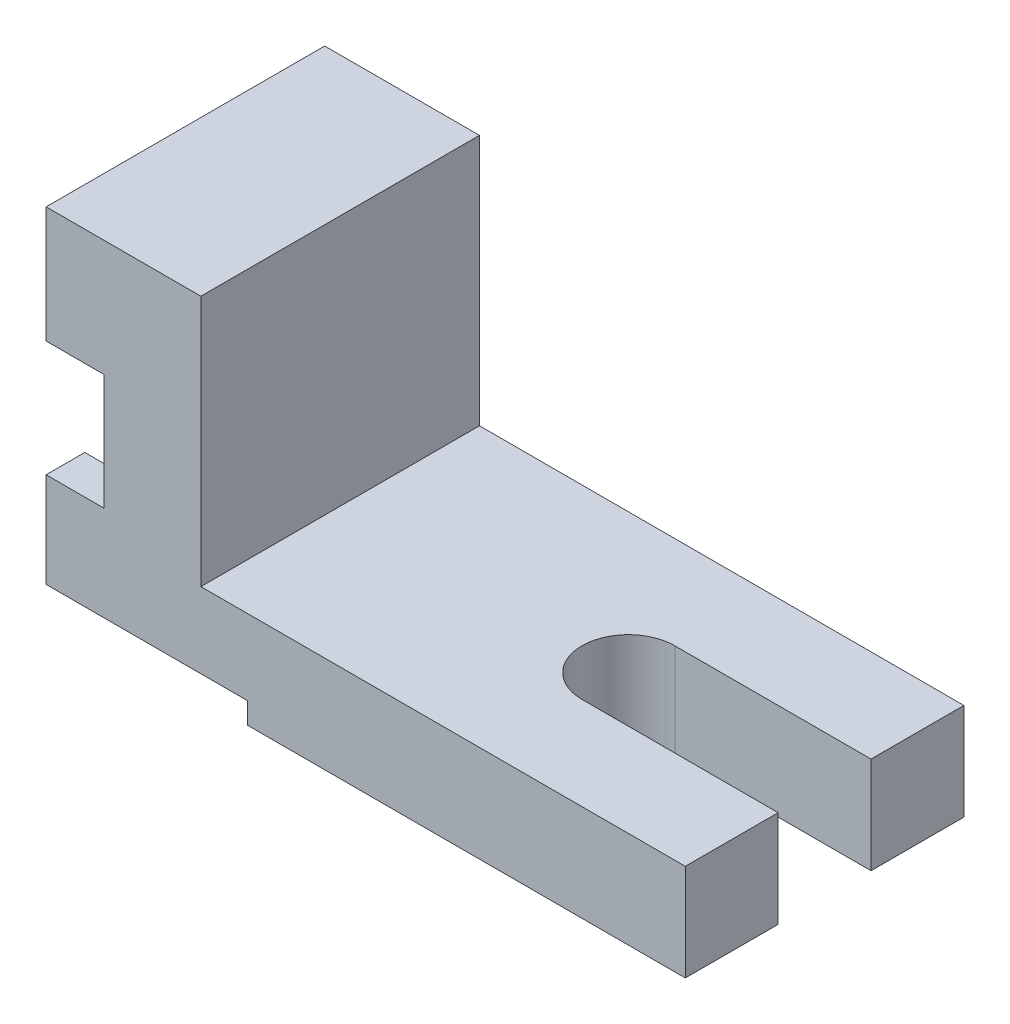
SolidWorks part; units mm, degrees
ref_plane "Front Plane" through (0, 0, 0) normal (0, 0, 1) x (1, 0, 0)
ref_plane "Top Plane" through (0, 0, 0) normal (0, 1, 0) x (1, 0, 0)
ref_plane "Right Plane" through (0, 0, 0) normal (1, 0, 0) x (0, 0, -1)
sketch "Sketch2" plane through (0, 0, 0) normal (0, 1, 0) x (1, 0, 0)
  line L0 (0, 0) -> (62.5979, 0)
  line L3 (62.5979, 0) -> (125.1959, 0)
  line L4 (125.1959, 0) -> (125.1959, 24)
  line L5 (125.1959, 24) -> (74.4742, 24)
  line L7 (74.4742, 48) -> (125.1959, 48)
  line L8 (125.1959, 48) -> (125.1959, 72)
  line L9 (125.1959, 72) -> (0, 72)
  line L10 (0, 72) -> (0, 0)
  arc A0 (74.4742, 48) -> (74.4742, 24) centre (74.4742, 36) ccw
  dimension "D1" = 24
  dimension "D2" = 24
  dimension "D3" = 24
extrude "Boss-Extrude1" add sketch "Sketch2" along normal blind 25
sketch "Sketch3" plane through (0, 0, 0) normal (-1, 0, 0) x (0, 0, 1)
  line L0 (-72, 0) -> (-72, 90)
  line L1 (-72, 90) -> (0, 90)
  line L2 (0, 90) -> (0, 0)
  line L3 (0, 0) -> (-72, 0)
  dimension "D1" = 90
extrude "Boss-Extrude2" add sketch "Sketch3" along normal blind 25
sketch "Sketch4" plane through (0, 0, 0) normal (0, 0, 1) x (1, 0, 0)
  line L0 (12.0599, 0) -> (12.0599, 5.4882)
  line L1 (-25, 0) -> (125.1959, 0) construction
  line L2 (12.0599, 5.4882) -> (-25, 5.4882)
  line L3 (-25, 0) -> (-25, 90) construction
  line L4 (-25, 5.4882) -> (-25, 0)
  line L5 (-25, 0) -> (12.0599, 0)
extrude "Cut-Extrude1" cut sketch "Sketch4" against normal blind 50
sketch "Sketch5" plane through (-25, 0, 0) normal (-1, 0, 0) x (0, 0, 1)
  line L0 (0, 5.4882) -> (-50, 5.4882)
  line L1 (-50, 5.4882) -> (-50, 0)
  line L2 (-50, 0) -> (-72, 0)
  line L3 (-72, 0) -> (-72, 30.0334)
  line L4 (-72, 90) -> (-72, 0) construction
  line L5 (-72, 30.0334) -> (-62, 30.0334)
  line L6 (0, 5.4882) -> (0, 30.0334)
  line L7 (0, 5.4882) -> (0, 90) construction
  line L8 (0, 30.0334) -> (-10, 30.0334)
  line L10 (-36, 97.2525) -> (-36, -12.1826) construction
  line L11 (-108.4734, 45) -> (20.8308, 45) construction
  line L12 (0, 90) -> (-72, 90) construction
  line L13 (-50, 90) -> (0, 90)
  line L14 (-72, 90) -> (-72, 59.9666)
  line L15 (-50, 90) -> (-72, 90)
  line L16 (0, 90) -> (0, 84.5118)
  line L17 (0, 84.5118) -> (0, 59.9666)
  line L18 (0, 59.9666) -> (-10, 59.9666)
  line L20 (-72, 59.9666) -> (-62, 59.9666)
  arc A0 (-62, 30.0334) -> (-10, 30.0334) centre (-36, 45) ccw
  arc A1 (-10, 59.9666) -> (-62, 59.9666) centre (-36, 45) ccw
  point P32 (0, 0)
  point P33 (0, 0)
  point P35 (0, 0)
  dimension "D3" = 10
  dimension "D6" = 30
  dimension "D1" = 36
  dimension "D2" = 45
  dimension "D4" = 10
  dimension "D5" = 10
extrude "Boss-Extrude3" add sketch "Sketch5" along normal blind 15
